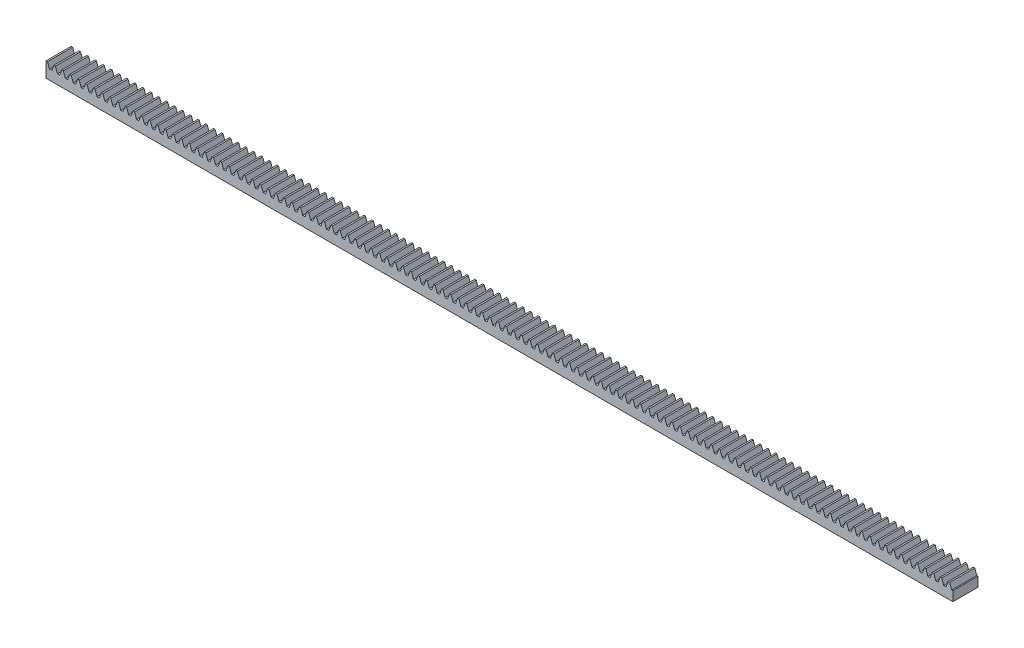
SolidWorks part; units mm, degrees
ref_plane "Front Plane" through (0, 0, 0) normal (0, 0, 1) x (1, 0, 0)
ref_plane "Top Plane" through (0, 0, 0) normal (0, 1, 0) x (1, 0, 0)
ref_plane "Right Plane" through (0, 0, 0) normal (1, 0, 0) x (0, 0, -1)
sketch "Sketch1" plane through (0, 0, 0) normal (0, 0, 1) x (1, 0, 0)
  line B0 (0, 0) -> (-228.6, 0)
  line B1 (0, 2.413) -> (0, 0)
  line B2 (-226.6138, 3.81) -> (-227.1223, 2.413)
  line B3 (-227.1223, 2.413) -> (-227.7175, 2.413)
  line B4 (-227.7175, 2.413) -> (-228.2259, 3.81)
  line B5 (-228.2259, 3.81) -> (-228.6, 3.81)
  line B6 (-228.6, 3.81) -> (-228.6, 0)
  line B7 (-228.6, 0) -> (0, 0)
  line B8 (0, 0) -> (0, 2.413)
  line B9 (0, 2.413) -> (-0.2976, 2.413)
  line B10 (-0.2976, 2.413) -> (-0.806, 3.81)
  line B11 (-0.806, 3.81) -> (-1.1889, 3.81)
  line B12 (-1.1889, 3.81) -> (-1.6973, 2.413)
  line B13 (-1.6973, 2.413) -> (-2.2925, 2.413)
  line B14 (-2.2925, 2.413) -> (-2.801, 3.81)
  line B15 (-2.801, 3.81) -> (-3.1838, 3.81)
  line B16 (-3.1838, 3.81) -> (-3.6922, 2.413)
  line B17 (-3.6922, 2.413) -> (-4.2874, 2.413)
  line B18 (-4.2874, 2.413) -> (-4.7959, 3.81)
  line B19 (-4.7959, 3.81) -> (-5.1787, 3.81)
  line B20 (-5.1787, 3.81) -> (-5.6872, 2.413)
  line B21 (-5.6872, 2.413) -> (-6.2823, 2.413)
  line B22 (-6.2823, 2.413) -> (-6.7908, 3.81)
  line B23 (-6.7908, 3.81) -> (-7.1736, 3.81)
  line B24 (-7.1736, 3.81) -> (-7.6821, 2.413)
  line B25 (-7.6821, 2.413) -> (-8.2772, 2.413)
  line B26 (-8.2772, 2.413) -> (-8.7857, 3.81)
  line B27 (-8.7857, 3.81) -> (-9.1685, 3.81)
  line B28 (-9.1685, 3.81) -> (-9.677, 2.413)
  line B29 (-9.677, 2.413) -> (-10.2721, 2.413)
  line B30 (-10.2721, 2.413) -> (-10.7806, 3.81)
  line B31 (-10.7806, 3.81) -> (-11.1634, 3.81)
  line B32 (-11.1634, 3.81) -> (-11.6719, 2.413)
  line B33 (-11.6719, 2.413) -> (-12.2671, 2.413)
  line B34 (-12.2671, 2.413) -> (-12.7755, 3.81)
  line B35 (-12.7755, 3.81) -> (-13.1583, 3.81)
  line B36 (-13.1583, 3.81) -> (-13.6668, 2.413)
  line B37 (-13.6668, 2.413) -> (-14.262, 2.413)
  line B38 (-14.262, 2.413) -> (-14.7704, 3.81)
  line B39 (-14.7704, 3.81) -> (-15.1532, 3.81)
  line B40 (-15.1532, 3.81) -> (-15.6617, 2.413)
  line B41 (-15.6617, 2.413) -> (-16.2569, 2.413)
  line B42 (-16.2569, 2.413) -> (-16.7653, 3.81)
  line B43 (-16.7653, 3.81) -> (-17.1482, 3.81)
  line B44 (-17.1482, 3.81) -> (-17.6566, 2.413)
  line B45 (-17.6566, 2.413) -> (-18.2518, 2.413)
  line B46 (-18.2518, 2.413) -> (-18.7603, 3.81)
  line B47 (-18.7603, 3.81) -> (-19.1431, 3.81)
  line B48 (-19.1431, 3.81) -> (-19.6515, 2.413)
  line B49 (-19.6515, 2.413) -> (-20.2467, 2.413)
  line B50 (-20.2467, 2.413) -> (-20.7552, 3.81)
  line B51 (-20.7552, 3.81) -> (-21.138, 3.81)
  line B52 (-21.138, 3.81) -> (-21.6464, 2.413)
  line B53 (-21.6464, 2.413) -> (-22.2416, 2.413)
  line B54 (-22.2416, 2.413) -> (-22.7501, 3.81)
  line B55 (-22.7501, 3.81) -> (-23.1329, 3.81)
  line B56 (-23.1329, 3.81) -> (-23.6414, 2.413)
  line B57 (-23.6414, 2.413) -> (-24.2365, 2.413)
  line B58 (-24.2365, 2.413) -> (-24.745, 3.81)
  line B59 (-24.745, 3.81) -> (-25.1278, 3.81)
  line B60 (-25.1278, 3.81) -> (-25.6363, 2.413)
  line B61 (-25.6363, 2.413) -> (-26.2314, 2.413)
  line B62 (-26.2314, 2.413) -> (-26.7399, 3.81)
  line B63 (-26.7399, 3.81) -> (-27.1227, 3.81)
  line B64 (-27.1227, 3.81) -> (-27.6312, 2.413)
  line B65 (-27.6312, 2.413) -> (-28.2263, 2.413)
  line B66 (-28.2263, 2.413) -> (-28.7348, 3.81)
  line B67 (-28.7348, 3.81) -> (-29.1176, 3.81)
  line B68 (-29.1176, 3.81) -> (-29.6261, 2.413)
  line B69 (-29.6261, 2.413) -> (-30.2213, 2.413)
  line B70 (-30.2213, 2.413) -> (-30.7297, 3.81)
  line B71 (-30.7297, 3.81) -> (-31.1125, 3.81)
  line B72 (-31.1125, 3.81) -> (-31.621, 2.413)
  line B73 (-31.621, 2.413) -> (-32.2162, 2.413)
  line B74 (-32.2162, 2.413) -> (-32.7246, 3.81)
  line B75 (-32.7246, 3.81) -> (-33.1074, 3.81)
  line B76 (-33.1074, 3.81) -> (-33.6159, 2.413)
  line B77 (-33.6159, 2.413) -> (-34.2111, 2.413)
  line B78 (-34.2111, 2.413) -> (-34.7195, 3.81)
  line B79 (-34.7195, 3.81) -> (-35.1024, 3.81)
  line B80 (-35.1024, 3.81) -> (-35.6108, 2.413)
  line B81 (-35.6108, 2.413) -> (-36.206, 2.413)
  line B82 (-36.206, 2.413) -> (-36.7145, 3.81)
  line B83 (-36.7145, 3.81) -> (-37.0973, 3.81)
  line B84 (-37.0973, 3.81) -> (-37.6057, 2.413)
  line B85 (-37.6057, 2.413) -> (-38.2009, 2.413)
  line B86 (-38.2009, 2.413) -> (-38.7094, 3.81)
  line B87 (-38.7094, 3.81) -> (-39.0922, 3.81)
  line B88 (-39.0922, 3.81) -> (-39.6006, 2.413)
  line B89 (-39.6006, 2.413) -> (-40.1958, 2.413)
  line B90 (-40.1958, 2.413) -> (-40.7043, 3.81)
  line B91 (-40.7043, 3.81) -> (-41.0871, 3.81)
  line B92 (-41.0871, 3.81) -> (-41.5956, 2.413)
  line B93 (-41.5956, 2.413) -> (-42.1907, 2.413)
  line B94 (-42.1907, 2.413) -> (-42.6992, 3.81)
  line B95 (-42.6992, 3.81) -> (-43.082, 3.81)
  line B96 (-43.082, 3.81) -> (-43.5905, 2.413)
  line B97 (-43.5905, 2.413) -> (-44.1856, 2.413)
  line B98 (-44.1856, 2.413) -> (-44.6941, 3.81)
  line B99 (-44.6941, 3.81) -> (-45.0769, 3.81)
  line B100 (-45.0769, 3.81) -> (-45.5854, 2.413)
  line B101 (-45.5854, 2.413) -> (-46.1805, 2.413)
  line B102 (-46.1805, 2.413) -> (-46.689, 3.81)
  line B103 (-46.689, 3.81) -> (-47.0718, 3.81)
  line B104 (-47.0718, 3.81) -> (-47.5803, 2.413)
  line B105 (-47.5803, 2.413) -> (-48.1755, 2.413)
  line B106 (-48.1755, 2.413) -> (-48.6839, 3.81)
  line B107 (-48.6839, 3.81) -> (-49.0667, 3.81)
  line B108 (-49.0667, 3.81) -> (-49.5752, 2.413)
  line B109 (-49.5752, 2.413) -> (-50.1704, 2.413)
  line B110 (-50.1704, 2.413) -> (-50.6788, 3.81)
  line B111 (-50.6788, 3.81) -> (-51.0616, 3.81)
  line B112 (-51.0616, 3.81) -> (-51.5701, 2.413)
  line B113 (-51.5701, 2.413) -> (-52.1653, 2.413)
  line B114 (-52.1653, 2.413) -> (-52.6737, 3.81)
  line B115 (-52.6737, 3.81) -> (-53.0566, 3.81)
  line B116 (-53.0566, 3.81) -> (-53.565, 2.413)
  line B117 (-53.565, 2.413) -> (-54.1602, 2.413)
  line B118 (-54.1602, 2.413) -> (-54.6687, 3.81)
  line B119 (-54.6687, 3.81) -> (-55.0515, 3.81)
  line B120 (-55.0515, 3.81) -> (-55.5599, 2.413)
  line B121 (-55.5599, 2.413) -> (-56.1551, 2.413)
  line B122 (-56.1551, 2.413) -> (-56.6636, 3.81)
  line B123 (-56.6636, 3.81) -> (-57.0464, 3.81)
  line B124 (-57.0464, 3.81) -> (-57.5548, 2.413)
  line B125 (-57.5548, 2.413) -> (-58.15, 2.413)
  line B126 (-58.15, 2.413) -> (-58.6585, 3.81)
  line B127 (-58.6585, 3.81) -> (-59.0413, 3.81)
  line B128 (-59.0413, 3.81) -> (-59.5498, 2.413)
  line B129 (-59.5498, 2.413) -> (-60.1449, 2.413)
  line B130 (-60.1449, 2.413) -> (-60.6534, 3.81)
  line B131 (-60.6534, 3.81) -> (-61.0362, 3.81)
  line B132 (-61.0362, 3.81) -> (-61.5447, 2.413)
  line B133 (-61.5447, 2.413) -> (-62.1398, 2.413)
  line B134 (-62.1398, 2.413) -> (-62.6483, 3.81)
  line B135 (-62.6483, 3.81) -> (-63.0311, 3.81)
  line B136 (-63.0311, 3.81) -> (-63.5396, 2.413)
  line B137 (-63.5396, 2.413) -> (-64.1347, 2.413)
  line B138 (-64.1347, 2.413) -> (-64.6432, 3.81)
  line B139 (-64.6432, 3.81) -> (-65.026, 3.81)
  line B140 (-65.026, 3.81) -> (-65.5345, 2.413)
  line B141 (-65.5345, 2.413) -> (-66.1297, 2.413)
  line B142 (-66.1297, 2.413) -> (-66.6381, 3.81)
  line B143 (-66.6381, 3.81) -> (-67.0209, 3.81)
  line B144 (-67.0209, 3.81) -> (-67.5294, 2.413)
  line B145 (-67.5294, 2.413) -> (-68.1246, 2.413)
  line B146 (-68.1246, 2.413) -> (-68.633, 3.81)
  line B147 (-68.633, 3.81) -> (-69.0158, 3.81)
  line B148 (-69.0158, 3.81) -> (-69.5243, 2.413)
  line B149 (-69.5243, 2.413) -> (-70.1195, 2.413)
  line B150 (-70.1195, 2.413) -> (-70.6279, 3.81)
  line B151 (-70.6279, 3.81) -> (-71.0108, 3.81)
  line B152 (-71.0108, 3.81) -> (-71.5192, 2.413)
  line B153 (-71.5192, 2.413) -> (-72.1144, 2.413)
  line B154 (-72.1144, 2.413) -> (-72.6229, 3.81)
  line B155 (-72.6229, 3.81) -> (-73.0057, 3.81)
  line B156 (-73.0057, 3.81) -> (-73.5141, 2.413)
  line B157 (-73.5141, 2.413) -> (-74.1093, 2.413)
  line B158 (-74.1093, 2.413) -> (-74.6178, 3.81)
  line B159 (-74.6178, 3.81) -> (-75.0006, 3.81)
  line B160 (-75.0006, 3.81) -> (-75.509, 2.413)
  line B161 (-75.509, 2.413) -> (-76.1042, 2.413)
  line B162 (-76.1042, 2.413) -> (-76.6127, 3.81)
  line B163 (-76.6127, 3.81) -> (-76.9955, 3.81)
  line B164 (-76.9955, 3.81) -> (-77.504, 2.413)
  line B165 (-77.504, 2.413) -> (-78.0991, 2.413)
  line B166 (-78.0991, 2.413) -> (-78.6076, 3.81)
  line B167 (-78.6076, 3.81) -> (-78.9904, 3.81)
  line B168 (-78.9904, 3.81) -> (-79.4989, 2.413)
  line B169 (-79.4989, 2.413) -> (-80.094, 2.413)
  line B170 (-80.094, 2.413) -> (-80.6025, 3.81)
  line B171 (-80.6025, 3.81) -> (-80.9853, 3.81)
  line B172 (-80.9853, 3.81) -> (-81.4938, 2.413)
  line B173 (-81.4938, 2.413) -> (-82.0889, 2.413)
  line B174 (-82.0889, 2.413) -> (-82.5974, 3.81)
  line B175 (-82.5974, 3.81) -> (-82.9802, 3.81)
  line B176 (-82.9802, 3.81) -> (-83.4887, 2.413)
  line B177 (-83.4887, 2.413) -> (-84.0839, 2.413)
  line B178 (-84.0839, 2.413) -> (-84.5923, 3.81)
  line B179 (-84.5923, 3.81) -> (-84.9751, 3.81)
  line B180 (-84.9751, 3.81) -> (-85.4836, 2.413)
  line B181 (-85.4836, 2.413) -> (-86.0788, 2.413)
  line B182 (-86.0788, 2.413) -> (-86.5872, 3.81)
  line B183 (-86.5872, 3.81) -> (-86.97, 3.81)
  line B184 (-86.97, 3.81) -> (-87.4785, 2.413)
  line B185 (-87.4785, 2.413) -> (-88.0737, 2.413)
  line B186 (-88.0737, 2.413) -> (-88.5821, 3.81)
  line B187 (-88.5821, 3.81) -> (-88.965, 3.81)
  line B188 (-88.965, 3.81) -> (-89.4734, 2.413)
  line B189 (-89.4734, 2.413) -> (-90.0686, 2.413)
  line B190 (-90.0686, 2.413) -> (-90.5771, 3.81)
  line B191 (-90.5771, 3.81) -> (-90.9599, 3.81)
  line B192 (-90.9599, 3.81) -> (-91.4683, 2.413)
  line B193 (-91.4683, 2.413) -> (-92.0635, 2.413)
  line B194 (-92.0635, 2.413) -> (-92.572, 3.81)
  line B195 (-92.572, 3.81) -> (-92.9548, 3.81)
  line B196 (-92.9548, 3.81) -> (-93.4633, 2.413)
  line B197 (-93.4633, 2.413) -> (-94.0584, 2.413)
  line B198 (-94.0584, 2.413) -> (-94.5669, 3.81)
  line B199 (-94.5669, 3.81) -> (-94.9497, 3.81)
  line B200 (-94.9497, 3.81) -> (-95.4582, 2.413)
  line B201 (-95.4582, 2.413) -> (-96.0533, 2.413)
  line B202 (-96.0533, 2.413) -> (-96.5618, 3.81)
  line B203 (-96.5618, 3.81) -> (-96.9446, 3.81)
  line B204 (-96.9446, 3.81) -> (-97.4531, 2.413)
  line B205 (-97.4531, 2.413) -> (-98.0482, 2.413)
  line B206 (-98.0482, 2.413) -> (-98.5567, 3.81)
  line B207 (-98.5567, 3.81) -> (-98.9395, 3.81)
  line B208 (-98.9395, 3.81) -> (-99.448, 2.413)
  line B209 (-99.448, 2.413) -> (-100.0431, 2.413)
  line B210 (-100.0431, 2.413) -> (-100.5516, 3.81)
  line B211 (-100.5516, 3.81) -> (-100.9344, 3.81)
  line B212 (-100.9344, 3.81) -> (-101.4429, 2.413)
  line B213 (-101.4429, 2.413) -> (-102.0381, 2.413)
  line B214 (-102.0381, 2.413) -> (-102.5465, 3.81)
  line B215 (-102.5465, 3.81) -> (-102.9293, 3.81)
  line B216 (-102.9293, 3.81) -> (-103.4378, 2.413)
  line B217 (-103.4378, 2.413) -> (-104.033, 2.413)
  line B218 (-104.033, 2.413) -> (-104.5414, 3.81)
  line B219 (-104.5414, 3.81) -> (-104.9243, 3.81)
  line B220 (-104.9243, 3.81) -> (-105.4327, 2.413)
  line B221 (-105.4327, 2.413) -> (-106.0279, 2.413)
  line B222 (-106.0279, 2.413) -> (-106.5363, 3.81)
  line B223 (-106.5363, 3.81) -> (-106.9192, 3.81)
  line B224 (-106.9192, 3.81) -> (-107.4276, 2.413)
  line B225 (-107.4276, 2.413) -> (-108.0228, 2.413)
  line B226 (-108.0228, 2.413) -> (-108.5313, 3.81)
  line B227 (-108.5313, 3.81) -> (-108.9141, 3.81)
  line B228 (-108.9141, 3.81) -> (-109.4225, 2.413)
  line B229 (-109.4225, 2.413) -> (-110.0177, 2.413)
  line B230 (-110.0177, 2.413) -> (-110.5262, 3.81)
  line B231 (-110.5262, 3.81) -> (-110.909, 3.81)
  line B232 (-110.909, 3.81) -> (-111.4175, 2.413)
  line B233 (-111.4175, 2.413) -> (-112.0126, 2.413)
  line B234 (-112.0126, 2.413) -> (-112.5211, 3.81)
  line B235 (-112.5211, 3.81) -> (-112.9039, 3.81)
  line B236 (-112.9039, 3.81) -> (-113.4124, 2.413)
  line B237 (-113.4124, 2.413) -> (-114.0075, 2.413)
  line B238 (-114.0075, 2.413) -> (-114.516, 3.81)
  line B239 (-114.516, 3.81) -> (-114.8988, 3.81)
  line B240 (-114.8988, 3.81) -> (-115.4073, 2.413)
  line B241 (-115.4073, 2.413) -> (-116.0024, 2.413)
  line B242 (-116.0024, 2.413) -> (-116.5109, 3.81)
  line B243 (-116.5109, 3.81) -> (-116.8937, 3.81)
  line B244 (-116.8937, 3.81) -> (-117.4022, 2.413)
  line B245 (-117.4022, 2.413) -> (-117.9974, 2.413)
  line B246 (-117.9974, 2.413) -> (-118.5058, 3.81)
  line B247 (-118.5058, 3.81) -> (-118.8886, 3.81)
  line B248 (-118.8886, 3.81) -> (-119.3971, 2.413)
  line B249 (-119.3971, 2.413) -> (-119.9923, 2.413)
  line B250 (-119.9923, 2.413) -> (-120.5007, 3.81)
  line B251 (-120.5007, 3.81) -> (-120.8835, 3.81)
  line B252 (-120.8835, 3.81) -> (-121.392, 2.413)
  line B253 (-121.392, 2.413) -> (-121.9872, 2.413)
  line B254 (-121.9872, 2.413) -> (-122.4956, 3.81)
  line B255 (-122.4956, 3.81) -> (-122.8785, 3.81)
  line B256 (-122.8785, 3.81) -> (-123.3869, 2.413)
  line B257 (-123.3869, 2.413) -> (-123.9821, 2.413)
  line B258 (-123.9821, 2.413) -> (-124.4906, 3.81)
  line B259 (-124.4906, 3.81) -> (-124.8734, 3.81)
  line B260 (-124.8734, 3.81) -> (-125.3818, 2.413)
  line B261 (-125.3818, 2.413) -> (-125.977, 2.413)
  line B262 (-125.977, 2.413) -> (-126.4855, 3.81)
  line B263 (-126.4855, 3.81) -> (-126.8683, 3.81)
  line B264 (-126.8683, 3.81) -> (-127.3767, 2.413)
  line B265 (-127.3767, 2.413) -> (-127.9719, 2.413)
  line B266 (-127.9719, 2.413) -> (-128.4804, 3.81)
  line B267 (-128.4804, 3.81) -> (-128.8632, 3.81)
  line B268 (-128.8632, 3.81) -> (-129.3717, 2.413)
  line B269 (-129.3717, 2.413) -> (-129.9668, 2.413)
  line B270 (-129.9668, 2.413) -> (-130.4753, 3.81)
  line B271 (-130.4753, 3.81) -> (-130.8581, 3.81)
  line B272 (-130.8581, 3.81) -> (-131.3666, 2.413)
  line B273 (-131.3666, 2.413) -> (-131.9617, 2.413)
  line B274 (-131.9617, 2.413) -> (-132.4702, 3.81)
  line B275 (-132.4702, 3.81) -> (-132.853, 3.81)
  line B276 (-132.853, 3.81) -> (-133.3615, 2.413)
  line B277 (-133.3615, 2.413) -> (-133.9566, 2.413)
  line B278 (-133.9566, 2.413) -> (-134.4651, 3.81)
  line B279 (-134.4651, 3.81) -> (-134.8479, 3.81)
  line B280 (-134.8479, 3.81) -> (-135.3564, 2.413)
  line B281 (-135.3564, 2.413) -> (-135.9516, 2.413)
  line B282 (-135.9516, 2.413) -> (-136.46, 3.81)
  line B283 (-136.46, 3.81) -> (-136.8428, 3.81)
  line B284 (-136.8428, 3.81) -> (-137.3513, 2.413)
  line B285 (-137.3513, 2.413) -> (-137.9465, 2.413)
  line B286 (-137.9465, 2.413) -> (-138.4549, 3.81)
  line B287 (-138.4549, 3.81) -> (-138.8377, 3.81)
  line B288 (-138.8377, 3.81) -> (-139.3462, 2.413)
  line B289 (-139.3462, 2.413) -> (-139.9414, 2.413)
  line B290 (-139.9414, 2.413) -> (-140.4498, 3.81)
  line B291 (-140.4498, 3.81) -> (-140.8327, 3.81)
  line B292 (-140.8327, 3.81) -> (-141.3411, 2.413)
  line B293 (-141.3411, 2.413) -> (-141.9363, 2.413)
  line B294 (-141.9363, 2.413) -> (-142.4448, 3.81)
  line B295 (-142.4448, 3.81) -> (-142.8276, 3.81)
  line B296 (-142.8276, 3.81) -> (-143.336, 2.413)
  line B297 (-143.336, 2.413) -> (-143.9312, 2.413)
  line B298 (-143.9312, 2.413) -> (-144.4397, 3.81)
  line B299 (-144.4397, 3.81) -> (-144.8225, 3.81)
  line B300 (-144.8225, 3.81) -> (-145.3309, 2.413)
  line B301 (-145.3309, 2.413) -> (-145.9261, 2.413)
  line B302 (-145.9261, 2.413) -> (-146.4346, 3.81)
  line B303 (-146.4346, 3.81) -> (-146.8174, 3.81)
  line B304 (-146.8174, 3.81) -> (-147.3259, 2.413)
  line B305 (-147.3259, 2.413) -> (-147.921, 2.413)
  line B306 (-147.921, 2.413) -> (-148.4295, 3.81)
  line B307 (-148.4295, 3.81) -> (-148.8123, 3.81)
  line B308 (-148.8123, 3.81) -> (-149.3208, 2.413)
  line B309 (-149.3208, 2.413) -> (-149.9159, 2.413)
  line B310 (-149.9159, 2.413) -> (-150.4244, 3.81)
  line B311 (-150.4244, 3.81) -> (-150.8072, 3.81)
  line B312 (-150.8072, 3.81) -> (-151.3157, 2.413)
  line B313 (-151.3157, 2.413) -> (-151.9108, 2.413)
  line B314 (-151.9108, 2.413) -> (-152.4193, 3.81)
  line B315 (-152.4193, 3.81) -> (-152.8021, 3.81)
  line B316 (-152.8021, 3.81) -> (-153.3106, 2.413)
  line B317 (-153.3106, 2.413) -> (-153.9058, 2.413)
  line B318 (-153.9058, 2.413) -> (-154.4142, 3.81)
  line B319 (-154.4142, 3.81) -> (-154.797, 3.81)
  line B320 (-154.797, 3.81) -> (-155.3055, 2.413)
  line B321 (-155.3055, 2.413) -> (-155.9007, 2.413)
  line B322 (-155.9007, 2.413) -> (-156.4091, 3.81)
  line B323 (-156.4091, 3.81) -> (-156.7919, 3.81)
  line B324 (-156.7919, 3.81) -> (-157.3004, 2.413)
  line B325 (-157.3004, 2.413) -> (-157.8956, 2.413)
  line B326 (-157.8956, 2.413) -> (-158.404, 3.81)
  line B327 (-158.404, 3.81) -> (-158.7869, 3.81)
  line B328 (-158.7869, 3.81) -> (-159.2953, 2.413)
  line B329 (-159.2953, 2.413) -> (-159.8905, 2.413)
  line B330 (-159.8905, 2.413) -> (-160.399, 3.81)
  line B331 (-160.399, 3.81) -> (-160.7818, 3.81)
  line B332 (-160.7818, 3.81) -> (-161.2902, 2.413)
  line B333 (-161.2902, 2.413) -> (-161.8854, 2.413)
  line B334 (-161.8854, 2.413) -> (-162.3939, 3.81)
  line B335 (-162.3939, 3.81) -> (-162.7767, 3.81)
  line B336 (-162.7767, 3.81) -> (-163.2851, 2.413)
  line B337 (-163.2851, 2.413) -> (-163.8803, 2.413)
  line B338 (-163.8803, 2.413) -> (-164.3888, 3.81)
  line B339 (-164.3888, 3.81) -> (-164.7716, 3.81)
  line B340 (-164.7716, 3.81) -> (-165.2801, 2.413)
  line B341 (-165.2801, 2.413) -> (-165.8752, 2.413)
  line B342 (-165.8752, 2.413) -> (-166.3837, 3.81)
  line B343 (-166.3837, 3.81) -> (-166.7665, 3.81)
  line B344 (-166.7665, 3.81) -> (-167.275, 2.413)
  line B345 (-167.275, 2.413) -> (-167.8701, 2.413)
  line B346 (-167.8701, 2.413) -> (-168.3786, 3.81)
  line B347 (-168.3786, 3.81) -> (-168.7614, 3.81)
  line B348 (-168.7614, 3.81) -> (-169.2699, 2.413)
  line B349 (-169.2699, 2.413) -> (-169.865, 2.413)
  line B350 (-169.865, 2.413) -> (-170.3735, 3.81)
  line B351 (-170.3735, 3.81) -> (-170.7563, 3.81)
  line B352 (-170.7563, 3.81) -> (-171.2648, 2.413)
  line B353 (-171.2648, 2.413) -> (-171.86, 2.413)
  line B354 (-171.86, 2.413) -> (-172.3684, 3.81)
  line B355 (-172.3684, 3.81) -> (-172.7512, 3.81)
  line B356 (-172.7512, 3.81) -> (-173.2597, 2.413)
  line B357 (-173.2597, 2.413) -> (-173.8549, 2.413)
  line B358 (-173.8549, 2.413) -> (-174.3633, 3.81)
  line B359 (-174.3633, 3.81) -> (-174.7461, 3.81)
  line B360 (-174.7461, 3.81) -> (-175.2546, 2.413)
  line B361 (-175.2546, 2.413) -> (-175.8498, 2.413)
  line B362 (-175.8498, 2.413) -> (-176.3582, 3.81)
  line B363 (-176.3582, 3.81) -> (-176.7411, 3.81)
  line B364 (-176.7411, 3.81) -> (-177.2495, 2.413)
  line B365 (-177.2495, 2.413) -> (-177.8447, 2.413)
  line B366 (-177.8447, 2.413) -> (-178.3532, 3.81)
  line B367 (-178.3532, 3.81) -> (-178.736, 3.81)
  line B368 (-178.736, 3.81) -> (-179.2444, 2.413)
  line B369 (-179.2444, 2.413) -> (-179.8396, 2.413)
  line B370 (-179.8396, 2.413) -> (-180.3481, 3.81)
  line B371 (-180.3481, 3.81) -> (-180.7309, 3.81)
  line B372 (-180.7309, 3.81) -> (-181.2393, 2.413)
  line B373 (-181.2393, 2.413) -> (-181.8345, 2.413)
  line B374 (-181.8345, 2.413) -> (-182.343, 3.81)
  line B375 (-182.343, 3.81) -> (-182.7258, 3.81)
  line B376 (-182.7258, 3.81) -> (-183.2343, 2.413)
  line B377 (-183.2343, 2.413) -> (-183.8294, 2.413)
  line B378 (-183.8294, 2.413) -> (-184.3379, 3.81)
  line B379 (-184.3379, 3.81) -> (-184.7207, 3.81)
  line B380 (-184.7207, 3.81) -> (-185.2292, 2.413)
  line B381 (-185.2292, 2.413) -> (-185.8243, 2.413)
  line B382 (-185.8243, 2.413) -> (-186.3328, 3.81)
  line B383 (-186.3328, 3.81) -> (-186.7156, 3.81)
  line B384 (-186.7156, 3.81) -> (-187.2241, 2.413)
  line B385 (-187.2241, 2.413) -> (-187.8192, 2.413)
  line B386 (-187.8192, 2.413) -> (-188.3277, 3.81)
  line B387 (-188.3277, 3.81) -> (-188.7105, 3.81)
  line B388 (-188.7105, 3.81) -> (-189.219, 2.413)
  line B389 (-189.219, 2.413) -> (-189.8142, 2.413)
  line B390 (-189.8142, 2.413) -> (-190.3226, 3.81)
  line B391 (-190.3226, 3.81) -> (-190.7054, 3.81)
  line B392 (-190.7054, 3.81) -> (-191.2139, 2.413)
  line B393 (-191.2139, 2.413) -> (-191.8091, 2.413)
  line B394 (-191.8091, 2.413) -> (-192.3175, 3.81)
  line B395 (-192.3175, 3.81) -> (-192.7004, 3.81)
  line B396 (-192.7004, 3.81) -> (-193.2088, 2.413)
  line B397 (-193.2088, 2.413) -> (-193.804, 2.413)
  line B398 (-193.804, 2.413) -> (-194.3124, 3.81)
  line B399 (-194.3124, 3.81) -> (-194.6953, 3.81)
  line B400 (-194.6953, 3.81) -> (-195.2037, 2.413)
  line B401 (-195.2037, 2.413) -> (-195.7989, 2.413)
  line B402 (-195.7989, 2.413) -> (-196.3074, 3.81)
  line B403 (-196.3074, 3.81) -> (-196.6902, 3.81)
  line B404 (-196.6902, 3.81) -> (-197.1986, 2.413)
  line B405 (-197.1986, 2.413) -> (-197.7938, 2.413)
  line B406 (-197.7938, 2.413) -> (-198.3023, 3.81)
  line B407 (-198.3023, 3.81) -> (-198.6851, 3.81)
  line B408 (-198.6851, 3.81) -> (-199.1936, 2.413)
  line B409 (-199.1936, 2.413) -> (-199.7887, 2.413)
  line B410 (-199.7887, 2.413) -> (-200.2972, 3.81)
  line B411 (-200.2972, 3.81) -> (-200.68, 3.81)
  line B412 (-200.68, 3.81) -> (-201.1885, 2.413)
  line B413 (-201.1885, 2.413) -> (-201.7836, 2.413)
  line B414 (-201.7836, 2.413) -> (-202.2921, 3.81)
  line B415 (-202.2921, 3.81) -> (-202.6749, 3.81)
  line B416 (-202.6749, 3.81) -> (-203.1834, 2.413)
  line B417 (-203.1834, 2.413) -> (-203.7785, 2.413)
  line B418 (-203.7785, 2.413) -> (-204.287, 3.81)
  line B419 (-204.287, 3.81) -> (-204.6698, 3.81)
  line B420 (-204.6698, 3.81) -> (-205.1783, 2.413)
  line B421 (-205.1783, 2.413) -> (-205.7734, 2.413)
  line B422 (-205.7734, 2.413) -> (-206.2819, 3.81)
  line B423 (-206.2819, 3.81) -> (-206.6647, 3.81)
  line B424 (-206.6647, 3.81) -> (-207.1732, 2.413)
  line B425 (-207.1732, 2.413) -> (-207.7684, 2.413)
  line B426 (-207.7684, 2.413) -> (-208.2768, 3.81)
  line B427 (-208.2768, 3.81) -> (-208.6596, 3.81)
  line B428 (-208.6596, 3.81) -> (-209.1681, 2.413)
  line B429 (-209.1681, 2.413) -> (-209.7633, 2.413)
  line B430 (-209.7633, 2.413) -> (-210.2717, 3.81)
  line B431 (-210.2717, 3.81) -> (-210.6546, 3.81)
  line B432 (-210.6546, 3.81) -> (-211.163, 2.413)
  line B433 (-211.163, 2.413) -> (-211.7582, 2.413)
  line B434 (-211.7582, 2.413) -> (-212.2667, 3.81)
  line B435 (-212.2667, 3.81) -> (-212.6495, 3.81)
  line B436 (-212.6495, 3.81) -> (-213.1579, 2.413)
  line B437 (-213.1579, 2.413) -> (-213.7531, 2.413)
  line B438 (-213.7531, 2.413) -> (-214.2616, 3.81)
  line B439 (-214.2616, 3.81) -> (-214.6444, 3.81)
  line B440 (-214.6444, 3.81) -> (-215.1528, 2.413)
  line B441 (-215.1528, 2.413) -> (-215.748, 2.413)
  line B442 (-215.748, 2.413) -> (-216.2565, 3.81)
  line B443 (-216.2565, 3.81) -> (-216.6393, 3.81)
  line B444 (-216.6393, 3.81) -> (-217.1478, 2.413)
  line B445 (-217.1478, 2.413) -> (-217.7429, 2.413)
  line B446 (-217.7429, 2.413) -> (-218.2514, 3.81)
  line B447 (-218.2514, 3.81) -> (-218.6342, 3.81)
  line B448 (-218.6342, 3.81) -> (-219.1427, 2.413)
  line B449 (-219.1427, 2.413) -> (-219.7378, 2.413)
  line B450 (-219.7378, 2.413) -> (-220.2463, 3.81)
  line B451 (-220.2463, 3.81) -> (-220.6291, 3.81)
  line B452 (-220.6291, 3.81) -> (-221.1376, 2.413)
  line B453 (-221.1376, 2.413) -> (-221.7327, 2.413)
  line B454 (-221.7327, 2.413) -> (-222.2412, 3.81)
  line B455 (-222.2412, 3.81) -> (-222.624, 3.81)
  line B456 (-222.624, 3.81) -> (-223.1325, 2.413)
  line B457 (-223.1325, 2.413) -> (-223.7277, 2.413)
  line B458 (-223.7277, 2.413) -> (-224.2361, 3.81)
  line B459 (-224.2361, 3.81) -> (-224.6189, 3.81)
  line B460 (-224.6189, 3.81) -> (-225.1274, 2.413)
  line B461 (-225.1274, 2.413) -> (-225.7226, 2.413)
  line B462 (-225.7226, 2.413) -> (-226.231, 3.81)
  line B463 (-226.231, 3.81) -> (-226.6138, 3.81)
sketch_block_instance "Rack-1"
sketch_block "Rack"
extrude "Boss-Extrude1" add sketch "Sketch1" along normal blind 6.35 contours B462 B463 B2 B3 B4 B5 B6 B0 B1 B9 B10 B11 B12 B13 B14 B15 B16 B17 B18 B19 B20 B21 B22 B23 B24 B25 B26 B27 B28 B29 B30 B31 B32 B33 B34 B35 B36 B37 B38 B39 B40 B41 B42 B43 B44 B45 B46 B47 B48 B49 B50
